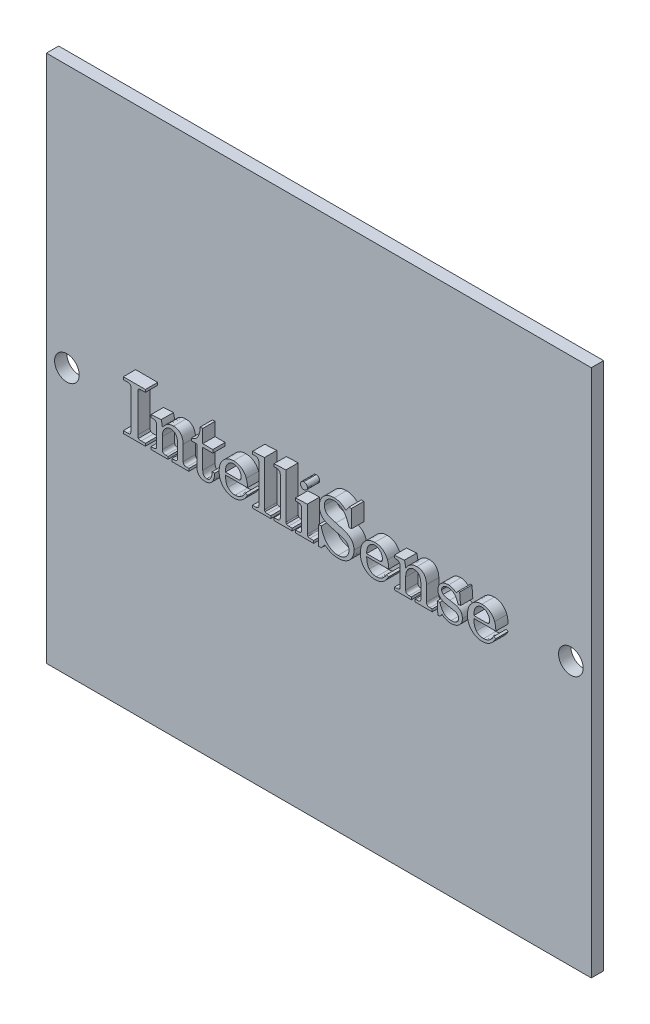
SolidWorks part; units mm, degrees
ref_plane "Front Plane" through (0, 0, 0) normal (0, 0, 1) x (1, 0, 0)
ref_plane "Top Plane" through (0, 0, 0) normal (0, 1, 0) x (1, 0, 0)
ref_plane "Right Plane" through (0, 0, 0) normal (1, 0, 0) x (0, 0, -1)
sketch "Sketch1" plane through (0, 0, 0) normal (0, 0, 1) x (1, 0, 0)
  line L5 (-33.25, 32.25) -> (33.25, 32.25)
  line L6 (-33.25, 32.25) -> (-33.25, -32.25)
  line L7 (-33.25, -32.25) -> (33.25, -32.25)
  line L8 (33.25, 32.25) -> (33.25, -32.25)
  line L9 (-33.25, 32.25) -> (33.25, -32.25) construction
  line L10 (-33.25, -32.25) -> (33.25, 32.25) construction
  point P0 (0, 0)
  dimension "D1" = 66.5
  dimension "D2" = 64.5
extrude "Boss-Extrude2" add sketch "Sketch1" along normal blind 1.5
sketch "Sketch3" plane through (0, 0, 1.5) normal (0, 0, 1) x (1, 0, 0)
  line L0 (33.25, 32.25) -> (-33.25, 32.25) construction
  line L2 (33.25, -32.25) -> (33.25, 32.25) construction
  line L3 (-33.25, 32.25) -> (-33.25, -32.25) construction
  line L4 (0, 31.4921) -> (0, -33.9404) construction
  line L6 (-33.25, -32.25) -> (33.25, -32.25) construction
  line L14 (-32.25, -32.25) -> (-32.25, -32.8324)
  circle A1 centre (-30.75, 0.23) radius 1.5
  circle A2 centre (30.75, 0) radius 1.5
  dimension "D5" = 32.25
  dimension "D1" = 32.02
  dimension "D4" = 32.25
  dimension "D2" = 32.48
  dimension "D3" = 2.5
  dimension "D6" = 2.5
extrude "Cut-Extrude1" cut sketch "Sketch3" against normal blind 1.5 contours A2 | A1
sketch "Sketch4" plane through (0, 0, 1.5) normal (0, 0, 1) x (1, 0, 0)
  text T0 "IntelliSense" font "Century Schoolbook" height 6
extrude "Boss-Extrude3" add sketch "Sketch4" along normal blind 1.5
